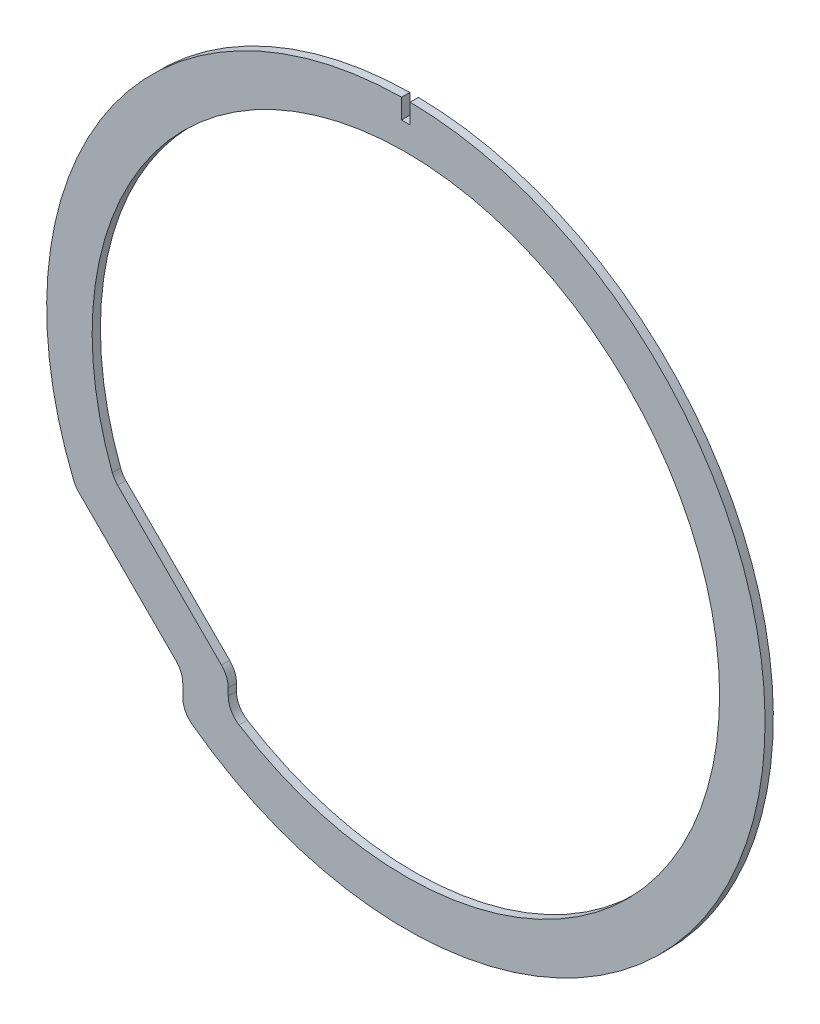
SolidWorks part; units mm, degrees
material "Balsa"
ref_plane "Front Plane" through (0, 0, 0) normal (0, 0, 1) x (1, 0, 0)
ref_plane "Top Plane" through (0, 0, 0) normal (0, 1, 0) x (1, 0, 0)
ref_plane "Right Plane" through (0, 0, 0) normal (1, 0, 0) x (0, 0, -1)
sketch "Sketch1" plane through (0, 0, 0) normal (0, 0, 1) x (1, 0, 0)
  line L0 (0, 32.094) -> (0, -346.2619) construction
  line L1 (0, 0) -> (0, 244.345) construction
  line L2 (0, 0) -> (0, 471.6969) construction
  line L3 (0, 0) -> (-283.5939, 0) construction
  line L4 (-127.2933, -32.5553) -> (-85.9841, -73.8644)
  line L5 (-85.9841, -73.8644) -> (-85.9841, -86.6438)
  line L6 (-85.9841, -73.8644) -> (-54.3993, -105.4493) construction
  arc A0 (-54.3993, -105.4493) -> (-127.2933, -32.5553) centre (0, 21.844) ccw
  arc A2 (-82.075, -89.6305) -> (-54.3993, -105.4493) centre (0, 21.844) ccw construction
  arc A3 (-127.2933, -32.5553) -> (-82.075, -89.6305) centre (0, 21.844) ccw construction
  arc A4 (-85.9841, -86.6438) -> (-54.3993, -105.4493) centre (0, 21.844) ccw
  spline S2 degree 3 poles (-474.9866, -3785.2451) (291.1547, -773.6329) (296.7292, 45.5132) (49.9381, 150.9258) (45.7097, 152.4909) (37.1079, 155.2035) (32.7346, 156.3511) (27.1752, 157.5183) (26.0587, 157.7384) (23.8163, 158.1514) (22.6888, 158.3447) (19.306, 158.8811) (17.0511, 159.1813) (10.2867, 159.9126) (1.2693, 160.4377) (-7.745, 160.0789) (-14.5046, 159.4749) (-16.7575, 159.2176) (-20.1367, 158.7464) (-21.263, 158.5751) (-23.5156, 158.2037) (-24.6421, 158.0036) (-30.2426, 156.9366) (-34.6466, 155.8674) (-43.3063, 153.3113) (-47.562, 151.8242) (-55.9254, 148.4331) (-60.0331, 146.529) (-66.0807, 143.3516) (-68.0818, 142.2359) (-72.0044, 139.9197) (-73.9301, 138.7173) (-79.6017, 134.9792) (-86.884, 129.6473) (-93.6143, 123.6295) (-98.4521, 118.8554) (-100.0296, 117.2204) (-102.3424, 114.7015) (-103.1054, 113.8496) (-104.6077, 112.1297) (-105.3467, 111.2623) (-108.9818, 106.8875) (-111.6981, 103.2683) (-116.7574, 95.7975) (-119.1004, 91.9459) (-123.4121, 84.0098) (-125.3809, 79.9253) (-127.6006, 74.6695) (-128.0327, 73.61) (-128.8681, 71.4874) (-129.2719, 70.423) (-130.4422, 67.2205) (-131.1674, 65.0732) (-133.1812, 58.5951) (-135.4347, 49.861) (-136.834, 40.9354) (-137.5569, 34.168) (-137.7434, 31.9) (-137.9397, 28.4793) (-137.9911, 27.3374) (-138.0656, 25.0596) (-138.0887, 23.9223) (-138.135, 18.2442) (-137.9496, 13.7276) (-137.1441, 4.7454) (-136.5239, 0.2797) (-134.8456, -8.6005) (-133.7876, -13.015) (-131.2181, -21.791) (-129.7278, -26.0794) (-126.351, -34.4622) (-124.4643, -38.5569) (-120.2966, -46.5538) (-118.0156, -50.456) (-114.9122, -55.2108) (-114.2789, -56.1556) (-112.9868, -58.0327) (-112.3272, -58.9661) (-110.315, -61.7398) (-108.9333, -63.5482) (-104.6702, -68.8537) (-98.6716, -75.6089) (-92.0553, -81.7381) (-86.8592, -86.0978) (-85.0881, -87.5114) (-82.3719, -89.5716) (-81.4566, -90.2482) (-79.6058, -91.5811) (-78.6696, -92.238) (199.3352, -282.1671) (1119.6458, 566.7419) (2795.5129, 2635.1063) knots -1.793342 -1.793342 -1.793342 -1.793342 0.03125 0.03125 0.0625 0.0625 0.09375 0.09375 0.101563 0.101563 0.109375 0.109375 0.125 0.125 0.15625 0.1875 0.1875 0.203125 0.203125 0.210937 0.210937 0.21875 0.21875 0.25 0.25 0.28125 0.28125 0.3125 0.3125 0.328125 0.328125 0.34375 0.34375 0.375 0.40625 0.40625 0.421875 0.421875 0.429687 0.429687 0.4375 0.4375 0.46875 0.46875 0.5 0.5 0.53125 0.53125 0.539062 0.539062 0.546875 0.546875 0.5625 0.5625 0.59375 0.625 0.625 0.640625 0.640625 0.648437 0.648437 0.65625 0.65625 0.6875 0.6875 0.71875 0.71875 0.75 0.75 0.78125 0.78125 0.8125 0.8125 0.84375 0.84375 0.851562 0.851562 0.859375 0.859375 0.875 0.875 0.90625 0.9375 0.9375 0.953125 0.953125 0.960937 0.960937 0.96875 0.96875 3.263053 3.263053 3.263053 3.263053 only from (66.3397, 143.1887) to (-66.0465, -100.0388)
  spline S3 degree 3 poles (66.3397, 143.1887) (62.3323, 145.3909) (58.2494, 147.3758) (49.9381, 150.9258) (45.7097, 152.4909) (37.1079, 155.2035) (32.7346, 156.3511) (27.1752, 157.5183) (26.0587, 157.7384) (23.8163, 158.1514) (22.6888, 158.3447) (19.306, 158.8811) (17.0511, 159.1813) (10.2867, 159.9126) (1.2693, 160.4377) (-7.745, 160.0789) (-14.5046, 159.4749) (-16.7575, 159.2176) (-20.1367, 158.7464) (-21.263, 158.5751) (-23.5156, 158.2037) (-24.6421, 158.0036) (-30.2426, 156.9366) (-34.6466, 155.8674) (-43.3063, 153.3113) (-47.562, 151.8242) (-55.9254, 148.4331) (-60.0331, 146.529) (-66.0807, 143.3516) (-68.0818, 142.2359) (-72.0044, 139.9197) (-73.9301, 138.7173) (-79.6017, 134.9792) (-86.884, 129.6473) (-93.6143, 123.6295) (-98.4521, 118.8554) (-100.0296, 117.2204) (-102.3424, 114.7015) (-103.1054, 113.8496) (-104.6077, 112.1297) (-105.3467, 111.2623) (-108.9818, 106.8875) (-111.6981, 103.2683) (-116.7574, 95.7975) (-119.1004, 91.9459) (-123.4121, 84.0098) (-125.3809, 79.9253) (-127.6006, 74.6695) (-128.0327, 73.61) (-128.8681, 71.4874) (-129.2719, 70.423) (-130.4422, 67.2205) (-131.1674, 65.0732) (-133.1812, 58.5951) (-135.4347, 49.861) (-136.834, 40.9354) (-137.5569, 34.168) (-137.7434, 31.9) (-137.9397, 28.4793) (-137.9911, 27.3374) (-138.0656, 25.0596) (-138.0887, 23.9223) (-138.135, 18.2442) (-137.9496, 13.7276) (-137.1441, 4.7454) (-136.5239, 0.2797) (-134.8456, -8.6005) (-133.7876, -13.015) (-131.2181, -21.791) (-129.7278, -26.0794) (-127.6847, -31.1513) (-127.3213, -32.0275) (-126.9491, -32.8995) knots 0 0 0 0 0.03125 0.03125 0.0625 0.0625 0.09375 0.09375 0.101563 0.101563 0.109375 0.109375 0.125 0.125 0.15625 0.1875 0.1875 0.203125 0.203125 0.210937 0.210937 0.21875 0.21875 0.25 0.25 0.28125 0.28125 0.3125 0.3125 0.328125 0.328125 0.34375 0.34375 0.375 0.40625 0.40625 0.421875 0.421875 0.429687 0.429687 0.4375 0.4375 0.46875 0.46875 0.5 0.5 0.53125 0.53125 0.539062 0.539062 0.546875 0.546875 0.5625 0.5625 0.59375 0.625 0.625 0.640625 0.640625 0.648437 0.648437 0.65625 0.65625 0.6875 0.6875 0.71875 0.71875 0.75 0.75 0.78125 0.78125 0.787815 0.787815 0.787815 0.787815 construction
  point P2 (0, 160.2226)
  point P3 (0, -116.9127)
  point P23 (-85.9841, -73.8644)
  dimension "D1" = 277.1353
  dimension "D2" = 276.86
  dimension "D3" = 21.844
  dimension "D5" = 45
  dimension "D6" = 113.03
  dimension "D4" = 58.42
  dimension "D7" = 45
extrude "Boss-Extrude1" add sketch "Sketch1" along normal mid plane 3.175
sketch "Sketch2" plane through (0, 0, 1.5875) normal (0, 0, 1) x (1, 0, 0)
  line L4 (-112.4231, -22.6399) -> (-68.4581, -66.6049)
  line L5 (-68.4581, -66.6049) -> (-68.4581, -77.8117)
  line L6 (-112.4231, -22.6399) -> (-68.4581, -66.6049)
  line L7 (-68.4581, -66.6049) -> (-68.4581, -77.8117)
  arc A2 (-68.4581, -77.8117) -> (-112.4231, -22.6399) centre (0, 21.844) ccw
  arc A3 (-68.4581, -77.8117) -> (-112.4231, -22.6399) centre (0, 21.844) ccw
  dimension "D1" = 17.526
extrude "Cut-Extrude1" cut sketch "Sketch2" against normal up to surface (3.175 mm away) up to face at (-27.5361, -9.1994, -1.5875)
fillet "Fillet1" radius 8.89 6 edges at (-127.2933, -32.5553, 0) (-112.4231, -22.6399, 0) (-85.9841, -73.8644, 0) (-85.9841, -86.6438, 0) (-68.4581, -66.6049, 0) (-68.4581, -77.8117, 0)
sketch "Sketch3" plane through (0, 0, 1.5875) normal (0, 0, 1) x (1, 0, 0)
  line L0 (-0.0002, 49.9919) -> (-0.0176, 733.2) construction
  line L1 (-0.0002, 49.9919) -> (-0.0176, 733.2) construction
  line L2 (-136.2041, -28.3557) -> (-0.0002, 49.9919) construction
  line L3 (136.2076, -28.3488) -> (-0.0002, 49.9919) construction
  line L4 (-136.2041, -28.3557) -> (-0.0002, 49.9919) construction
  line L5 (136.2076, -28.3488) -> (-0.0002, 49.9919) construction
  line L6 (-1.6539, 152.6441) -> (-1.654, 160.2641)
  line L7 (1.6481, 152.6442) -> (1.648, 160.2642)
  line L8 (-1.6539, 152.6441) -> (1.6481, 152.6442)
  line L11 (-126.0584, -33.7901) -> (-88.588, -71.2606)
  line L12 (-85.9841, -77.5468) -> (-85.9841, -82.2574)
  line L13 (-126.0584, -33.7901) -> (-88.588, -71.2606)
  line L14 (-85.9841, -77.5468) -> (-85.9841, -82.2574)
  arc A0 (-54.3993, -105.4493) -> (-127.2933, -32.5553) centre (0, 21.844) ccw construction
  arc A1 (-54.3993, -105.4493) -> (130.2841, -24.9419) centre (0, 21.844) ccw
  arc A2 (-1.654, 160.2641) -> (-130.2816, -24.9489) centre (0, 21.844) ccw construction
  arc A3 (-130.2816, -24.9489) -> (-127.2933, -32.5553) centre (0, 21.844) ccw
  arc A4 (-1.654, 160.2641) -> (-130.2816, -24.9489) centre (0, 21.844) ccw construction
  arc A5 (-130.2816, -24.9489) -> (-127.9919, -30.8906) centre (0, 21.844) ccw
  arc A6 (-82.3849, -89.4016) -> (-127.9919, -30.8906) centre (0, 21.844) ccw
  arc A7 (-127.9919, -30.8906) -> (-126.0584, -33.7901) centre (-119.7722, -27.504) ccw
  arc A8 (-85.9841, -77.5468) -> (-88.588, -71.2606) centre (-94.8741, -77.5468) ccw
  arc A9 (-85.9841, -82.2574) -> (-82.3849, -89.4016) centre (-77.0941, -82.2574) ccw
  arc A10 (-82.3849, -89.4016) -> (130.2841, -24.9419) centre (0, 21.844) ccw
  arc A11 (-127.9919, -30.8906) -> (-126.0584, -33.7901) centre (-119.7722, -27.504) ccw
  arc A12 (-85.9841, -77.5468) -> (-88.588, -71.2606) centre (-94.8741, -77.5468) ccw
  arc A13 (-85.9841, -82.2574) -> (-82.3849, -89.4016) centre (-77.0941, -82.2574) ccw
  arc A14 (130.2841, -24.9419) -> (1.648, 160.2642) centre (0, 21.844) ccw construction
  arc A15 (1.648, 160.2642) -> (-1.654, 160.2641) centre (0, 21.844) ccw
  arc A16 (130.2841, -24.9419) -> (1.648, 160.2642) centre (0, 21.844) ccw construction
  arc A17 (1.648, 160.2642) -> (-1.654, 160.2641) centre (0, 21.844) ccw
  arc M19 (-82.3849, -89.4016) -> (-127.9919, -30.8906) centre (0, 21.844) ccw
  dimension "D1" = 3.302
  dimension "D2" = 7.62
  dimension "D3" = 0
extrude "Cut-Extrude2" cut sketch "Sketch3" against normal through all contours L6 L8 L7 M19
